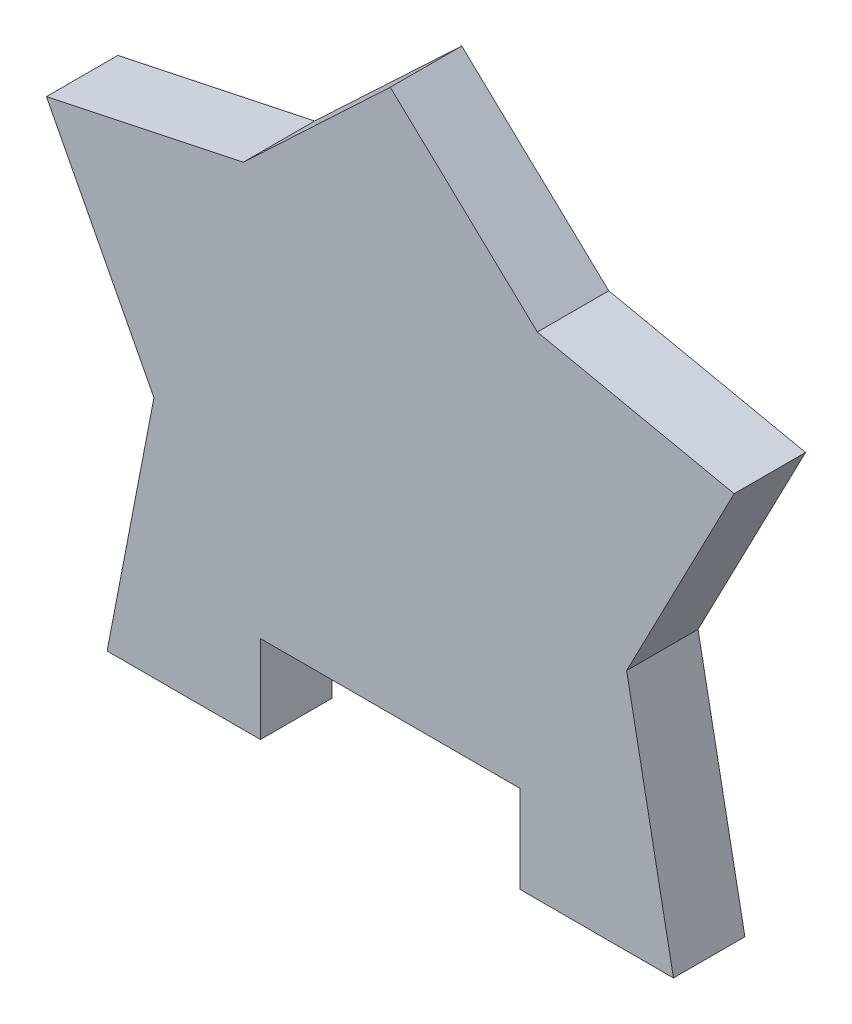
SolidWorks part; units mm, degrees
ref_plane "Plano frontal" through (0, 0, 0) normal (0, 0, 1) x (1, 0, 0)
ref_plane "Plano superior" through (0, 0, 0) normal (0, 1, 0) x (1, 0, 0)
ref_plane "Plano direito" through (0, 0, 0) normal (1, 0, 0) x (0, 0, -1)
sketch "Esboço1" plane through (0, 0, 0) normal (0, 0, 1) x (1, 0, 0)
  line L0 (0, -44.0993) -> (0, 44.0993) construction
  line L1 (0, 44.0993) -> (-20.5934, 24.7087)
  line L2 (-20.5934, 24.7087) -> (-48.1527, 18.8843)
  line L3 (-48.1527, 18.8843) -> (-33.0945, -10.0957)
  line L4 (-33.0945, -10.0957) -> (-39.6549, -44.0993)
  line L5 (-39.6549, -44.0993) -> (-18.1784, -44.0993)
  line L6 (-18.1784, -44.0993) -> (-18.1784, -31.848)
  line L7 (-18.1784, -31.848) -> (18.1784, -31.848)
  line L8 (18.1784, -44.0993) -> (18.1784, -31.848)
  line L9 (39.6549, -44.0993) -> (18.1784, -44.0993)
  line L10 (33.0945, -10.0957) -> (39.6549, -44.0993)
  line L11 (48.1527, 18.8843) -> (33.0945, -10.0957)
  line L12 (20.5934, 24.7087) -> (48.1527, 18.8843)
  line L13 (0, 44.0993) -> (20.5934, 24.7087)
  point P0 (-20.5934, 24.7087)
  point P4 (0, 0)
  point P13 (0, -31.848)
extrude "Ressalto-extrusão1" add sketch "Esboço1" along normal blind 10
